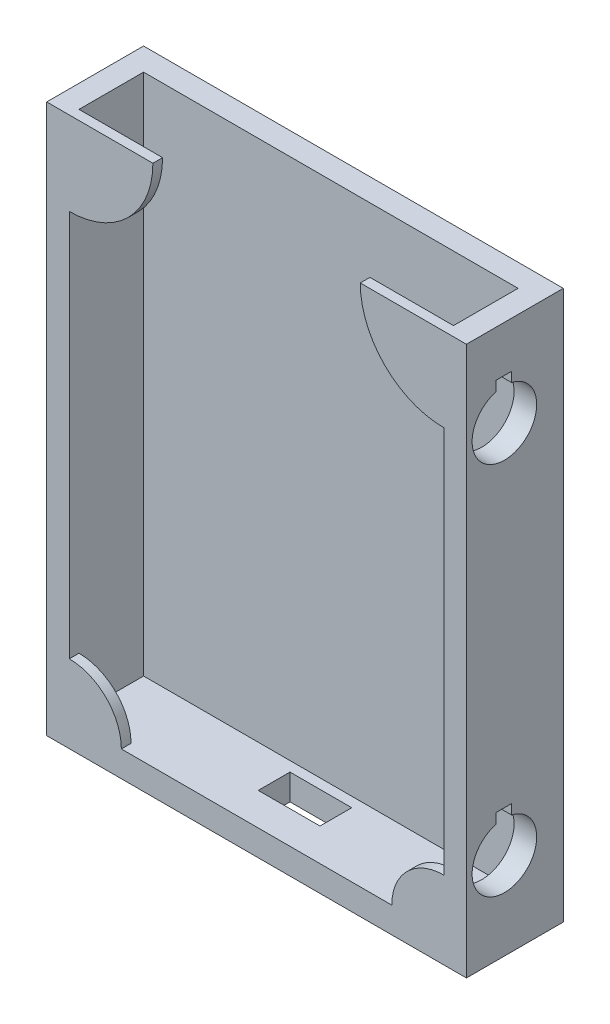
SolidWorks part; units mm, degrees
ref_plane "Plan de face" through (0, 0, 0) normal (0, 0, 1) x (1, 0, 0)
ref_plane "Plan de dessus" through (0, 0, 0) normal (0, 1, 0) x (1, 0, 0)
ref_plane "Plan de droite" through (0, 0, 0) normal (1, 0, 0) x (0, 0, -1)
sketch "Esquisse1" plane through (0, 0, 0) normal (0, 0, 1) x (1, 0, 0)
  line L1 (-80.2851, 28.1135) -> (-15.2851, 28.1135)
  line L2 (-80.2851, 28.1135) -> (-80.2851, -56.8865)
  line L3 (-80.2851, -56.8865) -> (-15.2851, -56.8865)
  line L4 (-15.2851, 28.1135) -> (-15.2851, -56.8865)
  dimension "D1" = 85
  dimension "D2" = 65
extrude "Boss.-Extru.1" add sketch "Esquisse1" along normal blind 15
sketch "Esquisse2" plane through (0, 0, 15) normal (0, 0, 1) x (1, 0, 0)
  line L0 (-80.2851, 28.1135) -> (-80.2851, -56.8865) construction
  line L1 (-76.7851, 15.1711) -> (-18.7851, 15.1711)
  line L2 (-76.7851, 15.1711) -> (-76.7851, -44.8289)
  line L3 (-76.7851, -44.8289) -> (-18.7851, -44.8289)
  line L4 (-18.7851, 15.1711) -> (-18.7851, -44.8289)
  line L5 (-15.2851, -56.8865) -> (-15.2851, 28.1135) construction
  dimension "D1" = 3.5
  dimension "D2" = 3.5
  dimension "D3" = 60
extrude "Enlèv. mat.-Extru.1" cut sketch "Esquisse2" against normal blind 11.5
sketch "Esquisse3" plane through (0, 0, 15) normal (0, 0, 1) x (1, 0, 0)
  line L0 (-15.2851, 28.1135) -> (-80.2851, 28.1135) construction
  line L1 (-63.8427, 28.1135) -> (-76.7851, 28.1135)
  line L2 (-76.7851, 28.1135) -> (-76.7851, 15.1711)
  line L3 (-31.7275, 28.1135) -> (-18.7851, 28.1135)
  line L4 (-80.2851, -52.8865) -> (-15.2851, -52.8865) construction
  line L5 (-80.2851, 28.1135) -> (-80.2851, -56.8865) construction
  line L6 (-15.2851, -56.8865) -> (-15.2851, 28.1135) construction
  line L7 (-80.2851, -56.8865) -> (-15.2851, -56.8865) construction
  line L8 (-76.7851, -44.8289) -> (-18.7851, -44.8289) construction
  line L9 (-76.7851, -44.8289) -> (-76.7851, -52.8865)
  line L10 (-68.7275, -52.8865) -> (-76.7851, -52.8865)
  line L11 (-18.7851, -44.8289) -> (-18.7851, -52.8865)
  line L12 (-26.8427, -52.8865) -> (-18.7851, -52.8865)
  line L13 (-76.7851, 15.1711) -> (-18.7851, 15.1711)
  line L14 (-63.8427, 28.1135) -> (-31.7275, 28.1135)
  line L15 (-76.7851, -44.8289) -> (-18.7851, -44.8289)
  line L16 (-26.8427, -52.8865) -> (-68.7275, -52.8865)
  arc A0 (-76.7851, 15.1711) -> (-63.8427, 28.1135) centre (-76.7851, 28.1135) ccw
  arc A1 (-18.7851, 15.1711) -> (-31.7275, 28.1135) centre (-18.7851, 28.1135) cw
  arc A2 (-76.7851, -44.8289) -> (-68.7275, -52.8865) centre (-76.7851, -52.8865) cw
  arc A3 (-18.7851, -44.8289) -> (-26.8427, -52.8865) centre (-18.7851, -52.8865) ccw
  line M2 (-76.7851, 15.1711) -> (-18.7851, 15.1711)
  line M4 (-18.7851, -44.8289) -> (-76.7851, -44.8289)
  line M8 (-15.2851, 28.1135) -> (-80.2851, 28.1135)
  dimension "D1" = 12.9424
  dimension "D2" = 4
extrude "Enlèv. mat.-Extru.2" cut sketch "Esquisse3" against normal blind 11.5 contours A1 A0 M2 M8 | A3 A2 L16 M4
sketch "Esquisse4" plane through (0, 28.1135, 0) normal (0, 1, 0) x (1, 0, 0)
  line L0 (-63.8427, -3.5) -> (-63.8427, -15) construction
  line L1 (-75.8576, -3.5) -> (-63.8427, -3.5)
  line L2 (-75.8576, -3.5) -> (-75.8576, -13.2622)
  line L3 (-75.8576, -13.2622) -> (-63.8427, -13.2622)
  line L4 (-63.8427, -3.5) -> (-63.8427, -13.2622)
  line L5 (-63.8427, -15) -> (-80.2851, -15) construction
  line L6 (-80.2851, -15) -> (-80.2851, 0) construction
  line L7 (-15.2851, 0) -> (-80.2851, 0) construction
  dimension "D1" = 1.7378
  dimension "D2" = 4.4275
  dimension "D3" = 3.5
sketch "Esquisse5" plane through (0, 28.1135, 0) normal (0, 1, 0) x (1, 0, 0)
  line L0 (-80.2851, -15) -> (-80.2851, 0) construction
  line L1 (-76.7851, -3.5) -> (-63.8427, -3.5)
  line L2 (-76.7851, -3.5) -> (-76.7851, -13.5)
  line L3 (-76.7851, -13.5) -> (-63.8427, -13.5)
  line L4 (-63.8427, -3.5) -> (-63.8427, -13.5)
  line L5 (-63.8427, -3.5) -> (-63.8427, -13.2622) construction
  line L6 (-15.2851, 0) -> (-80.2851, 0) construction
  line L7 (-63.8427, -15) -> (-80.2851, -15) construction
  point P10 (-72.0639, -15)
  dimension "D1" = 3.5
  dimension "D2" = 0
  dimension "D3" = 3.5
  dimension "D4" = 1.5
extrude "Enlèv. mat.-Extru.4" cut sketch "Esquisse5" against normal blind 81
sketch "Esquisse6" plane through (0, 28.1135, 0) normal (0, 1, 0) x (1, 0, 0)
  line L0 (-31.7275, -3.5) -> (-31.7275, -15) construction
  line L1 (-31.7275, -3.5) -> (-18.7851, -3.5)
  line L2 (-31.7275, -3.5) -> (-31.7275, -13.5)
  line L3 (-31.7275, -13.5) -> (-18.7851, -13.5)
  line L4 (-18.7851, -3.5) -> (-18.7851, -13.5)
  line L5 (-15.2851, -15) -> (-15.2851, 0) construction
  line L6 (-15.2851, 0) -> (-80.2851, 0) construction
  line L7 (-15.2851, -15) -> (-31.7275, -15) construction
  point P4 (-31.7275, -9.25)
  dimension "D1" = 0
  dimension "D2" = 3.5
  dimension "D3" = 3.5
  dimension "D4" = 1.5
extrude "Enlèv. mat.-Extru.5" cut sketch "Esquisse6" against normal blind 81
sketch "Esquisse7" plane through (0, -56.8865, 0) normal (0, -1, 0) x (-1, 0, 0)
  line L0 (80.2851, -15) -> (15.2851, -15) construction
  line L1 (47.7851, -15) -> (47.7851, 0) construction
  line L2 (80.2851, 0) -> (15.2851, 0) construction
  line L4 (52.5657, -9.9573) -> (43.0045, -9.9573)
  line L5 (52.5657, -9.9573) -> (52.5657, -5.0427)
  line L6 (52.5657, -5.0427) -> (43.0045, -5.0427)
  line L7 (43.0045, -9.9573) -> (43.0045, -5.0427)
  line L8 (52.5657, -9.9573) -> (43.0045, -5.0427) construction
  line L9 (52.5657, -5.0427) -> (43.0045, -9.9573) construction
  point P8 (47.7851, -7.5)
extrude "Enlèv. mat.-Extru.6" cut sketch "Esquisse7" against normal blind 81
sketch "Esquisse9" plane through (0, 0, 0) normal (0, 0, -1) x (-1, 0, 0)
  line L0 (47.7851, 28.1135) -> (47.7851, -56.8865) construction
  line L1 (15.2851, 28.1135) -> (80.2851, 28.1135) construction
  line L2 (80.2851, -56.8865) -> (15.2851, -56.8865) construction
  line L4 (34.2851, 15.1652) -> (61.2851, 15.1652)
  line L5 (34.2851, 15.1652) -> (34.2851, 0.1652)
  line L6 (34.2851, 0.1652) -> (61.2851, 0.1652)
  line L7 (61.2851, 15.1652) -> (61.2851, 0.1652)
  line L8 (34.2851, 15.1652) -> (61.2851, 0.1652) construction
  line L9 (34.2851, 0.1652) -> (61.2851, 15.1652) construction
  point P6 (47.7851, 7.6652)
  dimension "D1" = 15
  dimension "D2" = 27
extrude "Boss.-Extru.3" add sketch "Esquisse9" along normal blind 4
sketch "Esquisse10" plane through (0, 0, -4) normal (0, 0, -1) x (-1, 0, 0)
  line L0 (47.7851, 15.1652) -> (47.7851, 0.1652) construction
  line L1 (61.2851, 15.1652) -> (34.2851, 15.1652) construction
  line L2 (34.2851, 0.1652) -> (61.2851, 0.1652) construction
  line L3 (42.7851, 15.1652) -> (44.7851, 6.3652)
  line L4 (38.2851, 15.1652) -> (36.2851, 6.3652)
  line L5 (61.2851, 15.1652) -> (34.2851, 15.1652) construction
  line L6 (34.2851, 15.1652) -> (34.2851, 0.1652) construction
  line L7 (36.2851, 6.3652) -> (44.7851, 6.3652)
  line L8 (38.2851, 15.1652) -> (42.7851, 15.1652)
  line L9 (52.7851, 15.1652) -> (50.7851, 6.3652)
  line L10 (57.2851, 15.1652) -> (59.2851, 6.3652)
  line L11 (61.2851, 0.1652) -> (61.2851, 15.1652) construction
  line L12 (50.7851, 6.3652) -> (59.2851, 6.3652)
  line L13 (52.7851, 15.1652) -> (57.2851, 15.1652)
  dimension "D1" = 4
  dimension "D2" = 5
  dimension "D3" = 2
  dimension "D4" = 3
  dimension "D5" = 8.8
  dimension "D6" = 5
  dimension "D7" = 3
  dimension "D8" = 4
  dimension "D9" = 2
  dimension "D10" = 8.8
  dimension "D11" = 8.8
extrude "Enlèv. mat.-Extru.8" cut sketch "Esquisse10" against normal blind 4
sketch "Esquisse13" plane through (-15.2851, 0, 0) normal (1, 0, 0) x (0, 0, -1)
  line L0 (-7.5, -56.8865) -> (-7.5, 28.9541) construction
  line L1 (-15, -56.8865) -> (0, -56.8865) construction
  line L2 (-9.1183, 14.6135) -> (-10.4183, 14.5907) construction
  line L3 (-10.4183, 14.5907) -> (-8.0183, 14.5907)
  line L4 (-10.4183, 14.5907) -> (-10.4183, 20.9907)
  line L5 (-10.4183, 20.9907) -> (-8.0183, 20.9907)
  line L6 (-8.0183, 14.5907) -> (-8.0183, 20.9907)
  line L7 (0, 28.1135) -> (0, -56.8865) construction
  line L8 (0, -14.3865) -> (-15, -14.3865) construction
  line L9 (-15, -56.8865) -> (-15, 28.1135) construction
  line L11 (-10.4183, -36.9865) -> (-8.0183, -36.9865)
  line L12 (-10.4183, -36.9865) -> (-10.4183, -43.3865)
  line L13 (-10.4183, -43.3865) -> (-8.0183, -43.3865)
  line L14 (-8.0183, -36.9865) -> (-8.0183, -43.3865)
  circle A0 centre (-9.1183, 14.6135) radius 5
  circle A1 centre (-9.1183, -43.3865) radius 5
  dimension "D6" = 10
  dimension "D7" = 10
  dimension "D1" = 2.4
  dimension "D2" = 6.4
  dimension "D3" = 2.4
  dimension "D4" = 1.3
  dimension "D5" = 29
  dimension "D8" = 6.4
  dimension "D9" = 2.4
  dimension "D10" = 1.3
  dimension "D11" = 29
  dimension "D12" = 6.3772
extrude "Enlèv. mat.-Extru.9" cut sketch "Esquisse13" against normal blind 4 contours L4 A0 L6 L3 | L6 A0 L4 L3 | L12 A1 L14 L13 | L14 A1 L12 L13
